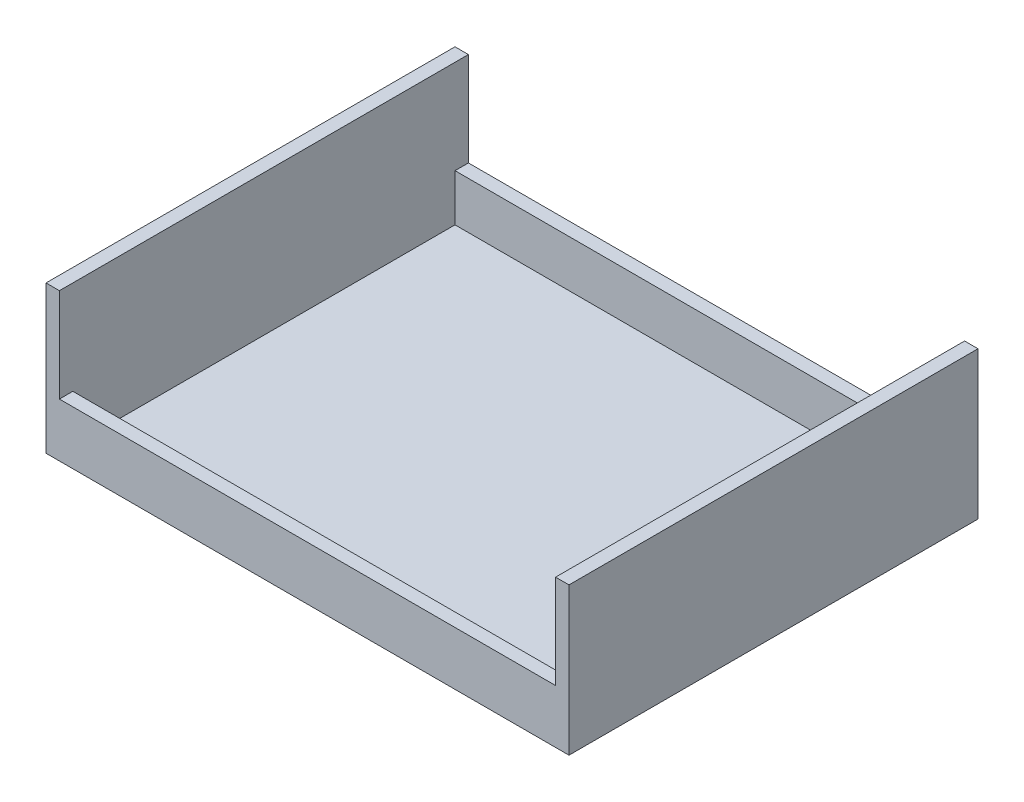
SolidWorks part; units mm, degrees
ref_plane "Front Plane" through (0, 0, 0) normal (0, 0, 1) x (1, 0, 0)
ref_plane "Top Plane" through (0, 0, 0) normal (0, 1, 0) x (1, 0, 0)
ref_plane "Right Plane" through (0, 0, 0) normal (1, 0, 0) x (0, 0, -1)
sketch "Sketch2" plane through (0, 0, 0) normal (0, 1, 0) x (1, 0, 0)
  line L1 (0, 0) -> (78, 0)
  line L2 (0, 0) -> (0, 61)
  line L3 (0, 61) -> (78, 61)
  line L4 (78, 0) -> (78, 61)
  dimension "D1" = 78
  dimension "D2" = 61
extrude "Boss-Extrude1" add sketch "Sketch2" along normal blind 1
sketch "Sketch3" plane through (0, 1, 0) normal (0, 1, 0) x (1, 0, 0)
  line L0 (78, 61) -> (0, 61) construction
  line L1 (0, 0) -> (2, 0)
  line L2 (0, 0) -> (0, 61)
  line L3 (0, 61) -> (2, 61)
  line L4 (2, 0) -> (2, 61)
  line L6 (78, 0) -> (76, 0)
  line L7 (78, 0) -> (78, 61)
  line L8 (78, 61) -> (76, 61)
  line L9 (76, 0) -> (76, 61)
  dimension "D1" = 2
extrude "Boss-Extrude2" add sketch "Sketch3" along normal blind 21
sketch "Sketch4" plane through (0, 1, 0) normal (0, 1, 0) x (1, 0, 0)
  line L0 (76, 61) -> (76, 0) construction
  line L1 (2, 0) -> (76, 0)
  line L2 (2, 0) -> (2, 2)
  line L3 (2, 2) -> (76, 2)
  line L4 (76, 0) -> (76, 2)
  line L5 (2, 0) -> (2, 61) construction
  line L6 (76, 61) -> (2, 61)
  line L7 (76, 61) -> (76, 59)
  line L8 (76, 59) -> (2, 59)
  line L9 (2, 61) -> (2, 59)
  dimension "D1" = 2
extrude "Boss-Extrude3" add sketch "Sketch4" along normal blind 7
